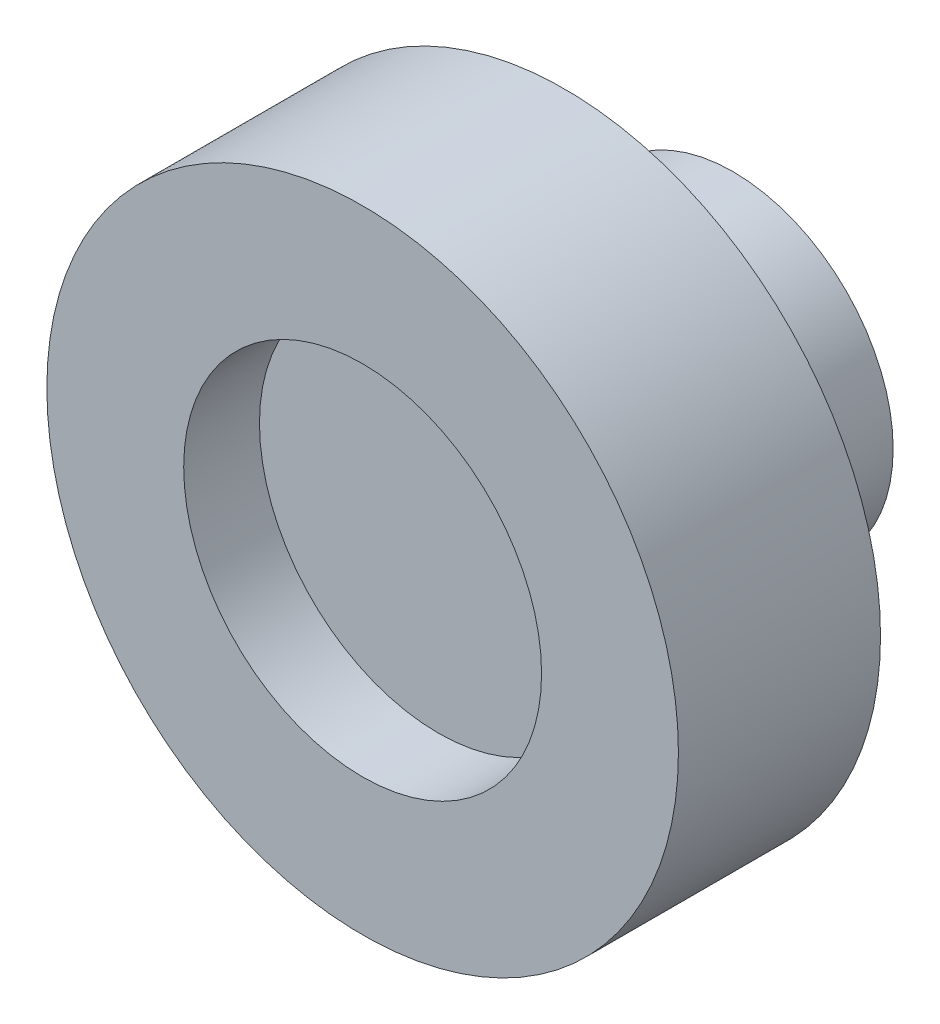
SolidWorks part; units mm, degrees
ref_plane "Płaszczyzna przednia" through (0, 0, 0) normal (0, 0, 1) x (1, 0, 0)
ref_plane "Płaszczyzna górna" through (0, 0, 0) normal (0, 1, 0) x (1, 0, 0)
ref_plane "Płaszczyzna prawa" through (0, 0, 0) normal (1, 0, 0) x (0, 0, -1)
sketch "Szkic1" plane through (0, 0, 0) normal (0, 0, 1) x (1, 0, 0)
  circle A0 centre (0, 0) radius 7.5
  dimension "D1" = 15
extrude "Dodanie-wyciągnięcie1" add sketch "Szkic1" along normal blind 3
sketch "Szkic2" plane through (0, 0, 0) normal (0, 0, -1) x (-1, 0, 0)
  circle A0 centre (0, 0) radius 3.8
  dimension "D1" = 7.6
extrude "Dodanie-wyciągnięcie2" add sketch "Szkic2" along normal blind 4
sketch "Szkic3" plane through (0, 0, 3) normal (0, 0, 1) x (1, 0, 0)
  circle A0 centre (0, 0) radius 4.25
  circle A1 centre (0, 0) radius 7.5
  dimension "D1" = 8.5
extrude "Dodanie-wyciągnięcie3" add sketch "Szkic3" along normal blind 1.8
